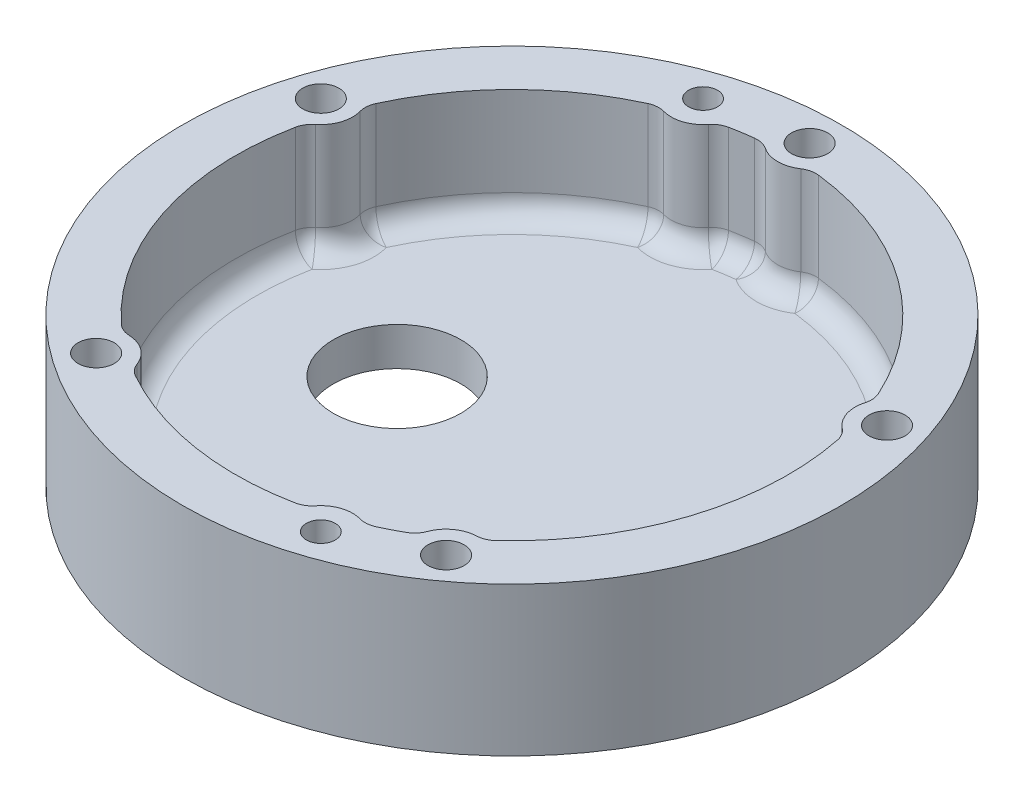
SolidWorks part; units mm, degrees
ref_plane "前视基准面" through (0, 0, 0) normal (0, 0, 1) x (1, 0, 0)
ref_plane "上视基准面" through (0, 0, 0) normal (0, 1, 0) x (1, 0, 0)
ref_plane "右视基准面" through (0, 0, 0) normal (1, 0, 0) x (0, 0, -1)
sketch "草图1" plane through (0, 0, 0) normal (0, 1, 0) x (1, 0, 0)
  circle A0 centre (0, 0) radius 77.5
  dimension "D1" = 155
extrude "凸台-拉伸1" add sketch "草图1" along normal blind 35
sketch "草图2" plane through (0, 0, 0) normal (0, 1, 0) x (1, 0, 0)
  circle A0 centre (0, 0) radius 70 construction
  point P3 (0, 70)
  dimension "D1" = 140
hole_wizard "孔1" positions "草图2" profile "草图3" legacy end condition through all
sketch "草图3" plane through (0, 0, -70) normal (1, 0, 0) x (0, 0, -1)
  line L0 (0, 0) -> (0, 35)
  line L1 (0, 35) -> (4.25, 35)
  line L2 (4.25, 35) -> (4.25, 9)
  line L3 (4.25, 9) -> (7, 9)
  line L4 (7, 9) -> (7, 0)
  line L5 (7, 0) -> (0, 0)
  line L6 (0, 110) -> (0, -10) construction
  dimension "直径" = 8.5
  dimension "深度" = 35
  dimension "柱坑直径" = 14
  dimension "柱坑深度" = 9
pattern_circular "阵列(圆周)1" count 5 over 360 about axis through (0, 0, 0) along (0, 1, 0) of "孔1"
sketch "草图4" plane through (0, 35, 0) normal (0, 1, 0) x (1, 0, 0)
  line L0 (0, 0) -> (-21.6312, 66.574) construction
  line L1 (0, -19.25) -> (0, 19.25) construction
  circle A0 centre (0, 0) radius 70 construction
  point P3 (-21.6312, 66.574)
  dimension "D1" = 140
  dimension "D2" = 18
hole_wizard "M8 螺纹孔1" positions "草图4" profile "草图5" tap size "M8" standard "GB" end condition through all
sketch "草图5" plane through (-21.6312, 35, -66.574) normal (1, 0, 0) x (0, 0, 1)
  line L0 (0, 0) -> (0, 35)
  line L1 (0, 35) -> (3.4, 35)
  line L2 (3.4, 35) -> (3.4, 0)
  line L5 (3.4, 0) -> (0, 0)
  line L11 (0, -6.35) -> (0, 107.95) construction
  dimension "通孔螺纹孔钻头直径" = 6.8
  dimension "通孔螺纹孔钻头深度" = 35
cosmetic thread "孔螺纹线1" parameters "D2"=8
pattern_circular "阵列(圆周)2" count 2 over 360 about axis through (0, 0, 0) along (0, 1, 0) of "M8 螺纹孔1"
cosmetic thread "孔螺纹线2" parameters "D2"=8
sketch "草图6" plane through (0, 35, 0) normal (0, 1, 0) x (1, 0, 0)
  arc A0 (59.9432, 25.1359) -> (5.3822, 64.7768) centre (0, 0) ccw
  arc A1 (-5.3822, 64.7768) -> (5.3822, 64.7768) centre (0, 70) ccw
  arc A2 (-25.1359, 59.9432) -> (-14.8984, 63.2696) centre (-21.6312, 66.574) ccw
  arc A3 (-63.2696, 14.8984) -> (-59.9432, 25.1359) centre (-66.574, 21.6312) ccw
  arc A4 (-33.7206, -55.5691) -> (-42.4291, -49.2419) centre (-41.145, -56.6312) ccw
  arc A5 (25.1359, -59.9432) -> (14.8984, -63.2696) centre (21.6312, -66.574) ccw
  arc A6 (42.4291, -49.2419) -> (33.7206, -55.5691) centre (41.145, -56.6312) ccw
  arc A7 (59.9432, 25.1359) -> (63.2696, 14.8984) centre (66.574, 21.6312) ccw
  arc A8 (5.3822, 64.7768) -> (-5.3822, 64.7768) centre (0, 70) ccw construction
  arc A9 (-14.8984, 63.2696) -> (-25.1359, 59.9432) centre (-21.6312, 66.574) ccw construction
  arc A10 (-59.9432, 25.1359) -> (-63.2696, 14.8984) centre (-66.574, 21.6312) ccw construction
  arc A11 (-42.4291, -49.2419) -> (-33.7206, -55.5691) centre (-41.145, -56.6312) ccw construction
  arc A12 (14.8984, -63.2696) -> (25.1359, -59.9432) centre (21.6312, -66.574) ccw construction
  arc A13 (33.7206, -55.5691) -> (42.4291, -49.2419) centre (41.145, -56.6312) ccw construction
  arc A14 (63.2696, 14.8984) -> (59.9432, 25.1359) centre (66.574, 21.6312) ccw construction
  arc A15 (63.2696, 14.8984) -> (59.9432, 25.1359) centre (0, 0) ccw construction
  arc A16 (5.3822, 64.7768) -> (-5.3822, 64.7768) centre (0, 0) ccw construction
  arc A17 (-5.3822, 64.7768) -> (-14.8984, 63.2696) centre (0, 0) ccw
  arc A18 (-14.8984, 63.2696) -> (-25.1359, 59.9432) centre (0, 0) ccw construction
  arc A19 (-25.1359, 59.9432) -> (-59.9432, 25.1359) centre (0, 0) ccw
  arc A20 (-59.9432, 25.1359) -> (-63.2696, 14.8984) centre (0, 0) ccw construction
  arc A21 (-63.2696, 14.8984) -> (-42.4291, -49.2419) centre (0, 0) ccw
  arc A22 (-42.4291, -49.2419) -> (-33.7206, -55.5691) centre (0, 0) ccw construction
  arc A23 (-33.7206, -55.5691) -> (14.8984, -63.2696) centre (0, 0) ccw
  arc A24 (14.8984, -63.2696) -> (25.1359, -59.9432) centre (0, 0) ccw construction
  arc A25 (25.1359, -59.9432) -> (33.7206, -55.5691) centre (0, 0) ccw
  arc A26 (33.7206, -55.5691) -> (42.4291, -49.2419) centre (0, 0) ccw construction
  arc A27 (42.4291, -49.2419) -> (63.2696, 14.8984) centre (0, 0) ccw
  dimension "D1" = 130
  dimension "D2" = 15
  dimension "D3" = 15
  dimension "D4" = 15
  dimension "D5" = 15
  dimension "D6" = 15
  dimension "D7" = 15
  dimension "D8" = 15
extrude "切除-拉伸1" cut sketch "草图6" against normal blind 26
fillet "圆角1" radius 5 28 edges at (-19.3136, 9, -59.441) (-10.1682, 9, -64.1997) (0, 9, -62.5) (38.206, 9, -52.5861) (59.441, 9, -19.3136) (61.8187, 9, 20.0861) (36.7366, 9, 50.5636) (29.5094, 9, 57.9154) (19.3136, 9, 59.441) (-10.1682, 9, 64.1997) (-36.7366, 9, 50.5636) (-61.8187, 9, 20.0861) (-59.441, 9, -19.3136) (-45.9619, 9, -45.9619) (-59.9432, 22, -25.1359) (-63.2696, 22, -14.8984) (-42.4291, 22, 49.2419) (-33.7206, 22, 55.5691) (14.8984, 22, 63.2696) (25.1359, 22, 59.9432) (33.7206, 22, 55.5691) (42.4291, 22, 49.2419) (63.2696, 22, -14.8984) (59.9432, 22, -25.1359) (5.3822, 22, -64.7768) (-5.3822, 22, -64.7768) (-25.1359, 22, -59.9432) (-14.8984, 22, -63.2696)
sketch "草图7" plane through (0, 9, 0) normal (0, 1, 0) x (1, 0, 0)
  line L0 (-19.25, 0) -> (19.25, 0) construction
  line L1 (0, -19.25) -> (0, 19.25) construction
  circle A0 centre (-27, 0) radius 15
  dimension "D1" = 30
  dimension "D2" = 27
extrude "切除-拉伸2" cut sketch "草图7" against normal through all
